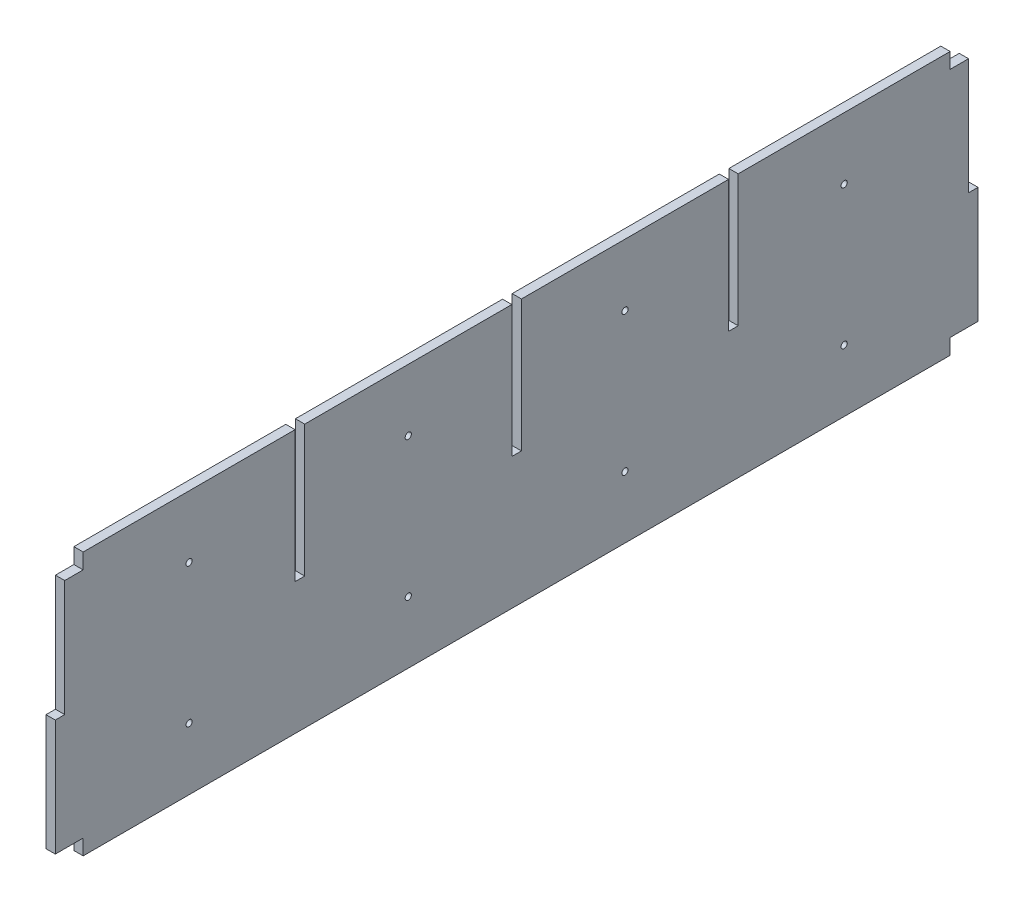
SolidWorks part; units mm, degrees
ref_plane "Front Plane" through (0, 0, 0) normal (0, 0, 1) x (1, 0, 0)
ref_plane "Top Plane" through (0, 0, 0) normal (0, 1, 0) x (1, 0, 0)
ref_plane "Right Plane" through (0, 0, 0) normal (1, 0, 0) x (0, 0, -1)
sketch "Sketch1" plane through (0, 0, 0) normal (1, 0, 0) x (0, 0, -1)
  line L0 (0, 0) -> (560, 0)
  line L1 (560, 0) -> (560, 10)
  line L2 (560, 10) -> (578, 10)
  line L3 (578, 10) -> (578, 85)
  line L4 (578, 85) -> (571.9, 85)
  line L5 (571.9, 85) -> (571.9, 160)
  line L6 (571.9, 160) -> (560, 160)
  line L7 (560, 160) -> (560, 170)
  line L8 (560, 170) -> (0, 170)
  line L9 (0, 170) -> (0, 160)
  line L10 (0, 160) -> (-11.9, 160)
  line L11 (-11.9, 160) -> (-11.9, 85)
  line L12 (-11.9, 85) -> (-18, 85)
  line L13 (-18, 85) -> (-18, 10)
  line L14 (0, 10) -> (0, 0)
  line L15 (-18, 10) -> (0, 10)
  dimension "D1" = 560
  dimension "D2" = 10
  dimension "D3" = 18
  dimension "D4" = 75
  dimension "D5" = 75
  dimension "D6" = 6.1
  dimension "D7" = 11.9
  dimension "D8" = 10
  dimension "D9" = 11.9
  dimension "D10" = 6.1
extrude "Boss-Extrude1" add sketch "Sketch1" along normal blind 6
sketch "Sketch2" plane through (6, 0, 0) normal (1, 0, 0) x (0, 0, -1)
  line L0 (560, 170) -> (0, 170) construction
  line L1 (136.9, 170) -> (143.1, 170)
  line L2 (136.9, 170) -> (136.9, 85)
  line L3 (136.9, 85) -> (143.1, 85)
  line L4 (143.1, 170) -> (143.1, 85)
  line L6 (276.9, 170) -> (283.1, 170)
  line L7 (276.9, 170) -> (276.9, 85)
  line L8 (276.9, 85) -> (283.1, 85)
  line L9 (283.1, 170) -> (283.1, 85)
  line L10 (416.9, 170) -> (423.1, 170)
  line L11 (416.9, 170) -> (416.9, 85)
  line L12 (416.9, 85) -> (423.1, 85)
  line L13 (423.1, 170) -> (423.1, 85)
  point P6 (140, 170)
  point P13 (280, 170)
  point P18 (420, 170)
  dimension "D1" = 0
  dimension "D2" = 140
  dimension "D3" = 6.2
  dimension "D4" = 140
  dimension "D5" = 6.2
  dimension "D6" = 140
  dimension "D7" = 6.2
extrude "Cut-Extrude1" cut sketch "Sketch2" against normal blind 6
sketch "Sketch3" plane through (6, 0, 0) normal (1, 0, 0) x (0, 0, -1)
  line L0 (136.9, 170) -> (0, 170) construction
  circle A0 centre (68.45, 130) radius 2
  circle A1 centre (68.45, 40) radius 2
  circle A2 centre (210, 130) radius 2
  circle A3 centre (210, 40) radius 2
  circle A4 centre (350, 130) radius 2
  circle A5 centre (350, 40) radius 2
  circle A6 centre (491.55, 130) radius 2
  circle A7 centre (491.55, 40) radius 2
  point P4 (68.45, 170)
  dimension "D2" = 4
  dimension "D5" = 4
  dimension "D6" = 4
  dimension "D7" = 4
  dimension "D8" = 4
  dimension "D9" = 4
  dimension "D10" = 4
  dimension "D11" = 4
  dimension "D1" = 0
  dimension "D3" = 30
  dimension "D4" = 30
extrude "Cut-Extrude2" cut sketch "Sketch3" against normal blind 6
